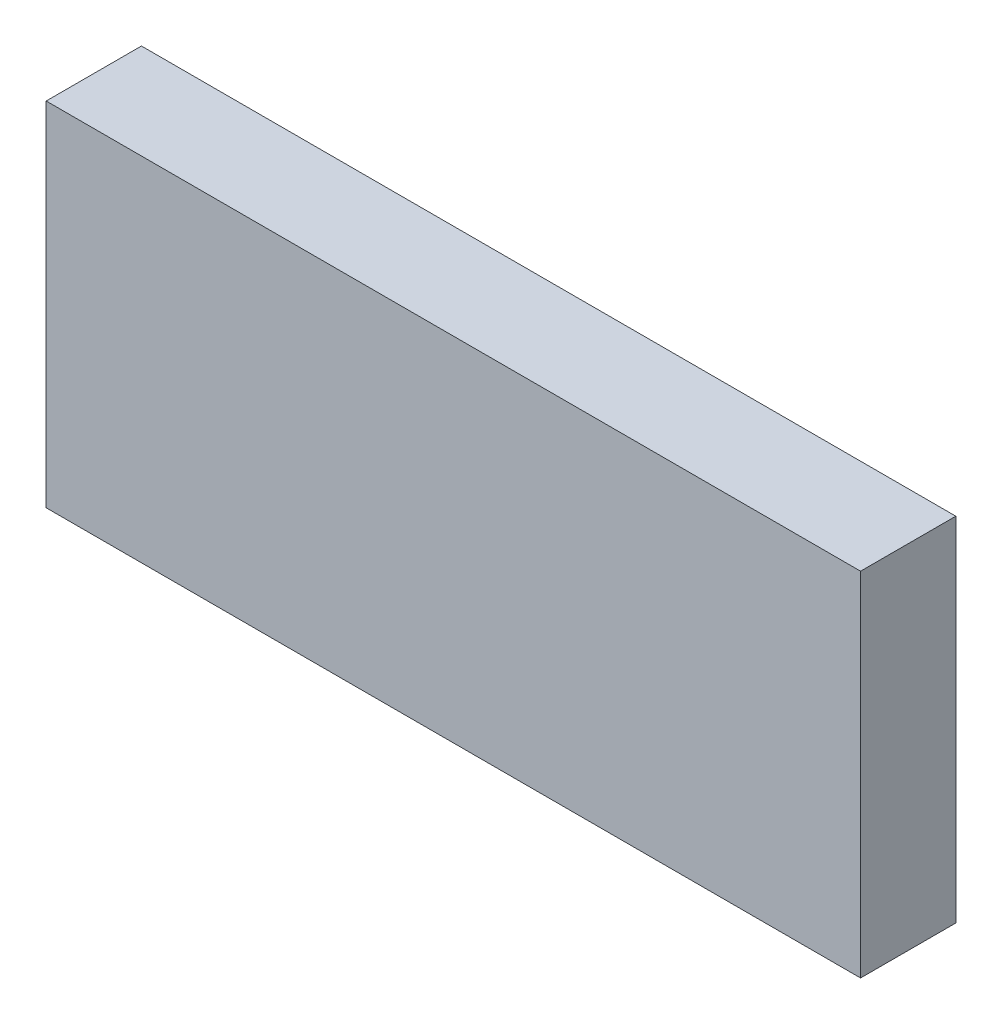
SolidWorks part; units mm, degrees
ref_plane "Front Plane" through (0, 0, 0) normal (1, 0, 0) x (0, 1, 0)
ref_plane "Top Plane" through (0, 0, 0) normal (0, 0, 1) x (0, 1, 0)
ref_plane "Right Plane" through (0, 0, 0) normal (0, 1, 0) x (-1, 0, 0)
sketch "Sketch1" plane through (0, 0, 0) normal (0, 0, 1) x (0, 1, 0)
  line L1 (-18.4943, -42.749) -> (18.4943, -42.749)
  line L2 (-18.4943, -42.749) -> (-18.4943, 42.749)
  line L3 (-18.4943, 42.749) -> (18.4943, 42.749)
  line L4 (18.4943, -42.749) -> (18.4943, 42.749)
  line L5 (-18.4943, -42.749) -> (18.4943, 42.749) construction
  line L6 (-18.4943, 42.749) -> (18.4943, -42.749) construction
  point P0 (0, 0)
extrude "Boss-Extrude1" add sketch "Sketch1" along normal blind 10
